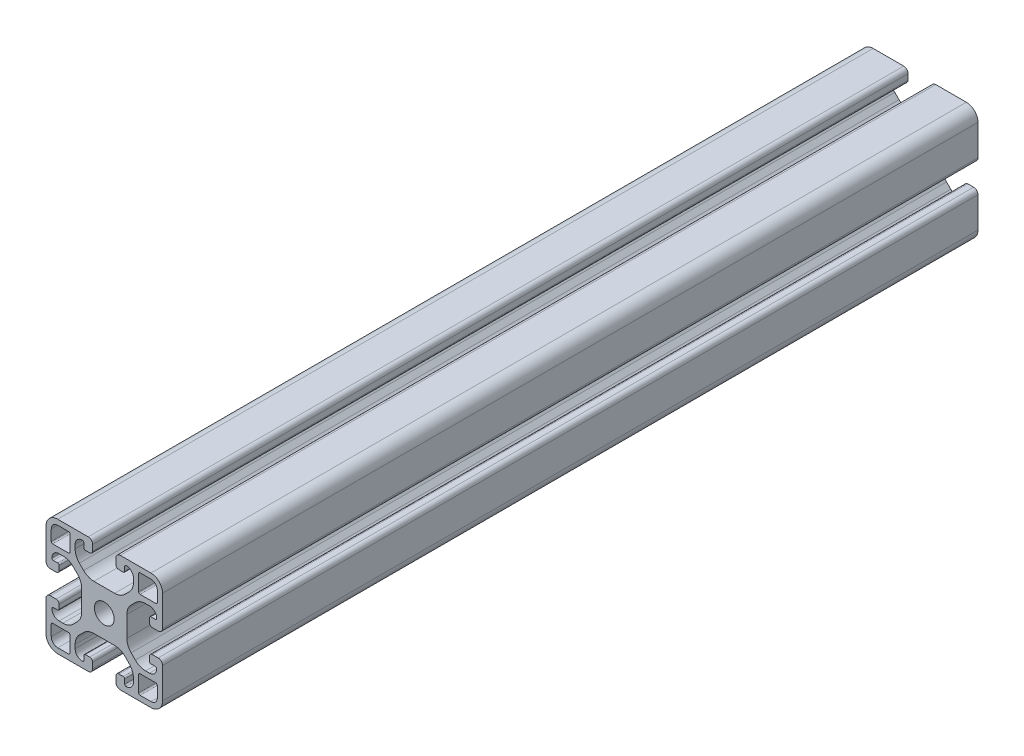
SolidWorks part; units mm, degrees
ref_plane "Plan de face" through (0, 0, 0) normal (0, 0, 1) x (1, 0, 0)
ref_plane "Plan de dessus" through (0, 0, 0) normal (0, 1, 0) x (1, 0, 0)
ref_plane "Plan de droite" through (0, 0, 0) normal (1, 0, 0) x (0, 0, -1)
ref_plane "Plan1" through (0, 0, -30) normal (0, 0, -1) x (-1, 0, 0)
sketch "Esquisse1" plane through (0, 0, -30) normal (0, 0, -1) x (-1, 0, 0)
  line L0 (-4.5, 15) -> (-4.5, 13.5)
  line L1 (-4, 13) -> (-2.5, 13)
  line L2 (-4.5, 10) -> (-5.8076, 10)
  line L3 (-9.3431, 11.4645) -> (-10.7855, 12.9069)
  line L4 (-12.25, 16.4424) -> (-12.25, 23.5576)
  line L5 (-10.7855, 27.0931) -> (-9.3431, 28.5355)
  line L6 (-5.8076, 30) -> (-4.5, 30)
  line L7 (-2.5, 27) -> (-4, 27)
  line L8 (-4.5, 26.5) -> (-4.5, 25)
  line L9 (-3.5, 24) -> (-1.5, 24)
  line L10 (0, 25.5) -> (0, 36)
  line L11 (-4, 40) -> (-14.5, 40)
  line L12 (-16, 38.5) -> (-16, 36.5)
  line L13 (-15, 35.5) -> (-13.5, 35.5)
  line L14 (-13, 36) -> (-13, 37.5)
  line L15 (-10, 35.5) -> (-10, 34.1924)
  line L16 (-11.4645, 30.6569) -> (-12.9069, 29.2145)
  line L17 (-16.4424, 27.75) -> (-23.5576, 27.75)
  line L18 (-27.0931, 29.2145) -> (-28.5355, 30.6569)
  line L19 (-30, 34.1924) -> (-30, 35.5)
  line L20 (-27, 37.5) -> (-27, 36)
  line L21 (-26.5, 35.5) -> (-25, 35.5)
  line L22 (-24, 36.5) -> (-24, 38.5)
  line L23 (-25.5, 40) -> (-36, 40)
  line L24 (-40, 36) -> (-40, 25.5)
  line L25 (-38.5, 24) -> (-36.5, 24)
  line L26 (-35.5, 25) -> (-35.5, 26.5)
  line L27 (-36, 27) -> (-37.5, 27)
  line L28 (-35.5, 30) -> (-34.1924, 30)
  line L29 (-30.6569, 28.5355) -> (-29.2145, 27.0931)
  line L30 (-27.75, 23.5576) -> (-27.75, 16.4424)
  line L31 (-29.2145, 12.9069) -> (-30.6569, 11.4645)
  line L32 (-34.1924, 10) -> (-35.5, 10)
  line L33 (-37.5, 13) -> (-36, 13)
  line L34 (-35.5, 13.5) -> (-35.5, 15)
  line L35 (-36.5, 16) -> (-38.5, 16)
  line L36 (-40, 14.5) -> (-40, 4)
  line L37 (-36, 0) -> (-25.5, 0)
  line L38 (-24, 1.5) -> (-24, 3.5)
  line L39 (-25, 4.5) -> (-26.5, 4.5)
  line L40 (-27, 4) -> (-27, 2.5)
  line L41 (-30, 4.5) -> (-30, 5.8076)
  line L42 (-28.5355, 9.3431) -> (-27.0931, 10.7855)
  line L43 (-23.5576, 12.25) -> (-16.4424, 12.25)
  line L44 (-12.9069, 10.7855) -> (-11.4645, 9.3431)
  line L45 (-10, 5.8076) -> (-10, 4.5)
  line L46 (-13, 2.5) -> (-13, 4)
  line L47 (-13.5, 4.5) -> (-15, 4.5)
  line L48 (-16, 3.5) -> (-16, 1.5)
  line L49 (-14.5, 0) -> (-4, 0)
  line L50 (0, 4) -> (0, 14.5)
  line L51 (-1.5, 16) -> (-3.5, 16)
  line L52 (-4, 1.8) -> (-7.7, 1.8)
  line L53 (-8.2, 2.3) -> (-8.2, 7.7)
  line L54 (-7.7, 8.2) -> (-2.3, 8.2)
  line L55 (-1.8, 7.7) -> (-1.8, 4)
  line L56 (-38.2, 4) -> (-38.2, 7.7)
  line L57 (-37.7, 8.2) -> (-32.3, 8.2)
  line L58 (-31.8, 7.7) -> (-31.8, 2.3)
  line L59 (-32.3, 1.8) -> (-36, 1.8)
  line L60 (-36, 38.2) -> (-32.3, 38.2)
  line L61 (-31.8, 37.7) -> (-31.8, 32.3)
  line L62 (-32.3, 31.8) -> (-37.7, 31.8)
  line L63 (-38.2, 32.3) -> (-38.2, 36)
  line L64 (-1.8, 36) -> (-1.8, 32.3)
  line L65 (-2.3, 31.8) -> (-7.7, 31.8)
  line L66 (-8.2, 32.3) -> (-8.2, 37.7)
  line L67 (-7.7, 38.2) -> (-4, 38.2)
  arc A0 (-4.5, 13.5) -> (-4, 13) centre (-4, 13.5) ccw
  arc A1 (-2.5, 13) -> (-2, 12.5) centre (-2.5, 12.5) cw
  arc A2 (-2, 12.5) -> (-4.5, 10) centre (-4.5, 12.5) cw
  arc A3 (-5.8076, 10) -> (-9.3431, 11.4645) centre (-5.8076, 15) cw
  arc A4 (-10.7855, 12.9069) -> (-12.25, 16.4424) centre (-7.25, 16.4424) cw
  arc A5 (-12.25, 23.5576) -> (-10.7855, 27.0931) centre (-7.25, 23.5576) cw
  arc A6 (-9.3431, 28.5355) -> (-5.8076, 30) centre (-5.8076, 25) cw
  arc A7 (-4.5, 30) -> (-2, 27.5) centre (-4.5, 27.5) cw
  arc A8 (-2, 27.5) -> (-2.5, 27) centre (-2.5, 27.5) cw
  arc A9 (-4, 27) -> (-4.5, 26.5) centre (-4, 26.5) ccw
  arc A10 (-4.5, 25) -> (-3.5, 24) centre (-3.5, 25) ccw
  arc A11 (-1.5, 24) -> (0, 25.5) centre (-1.5, 25.5) ccw
  arc A12 (0, 36) -> (-4, 40) centre (-4, 36) ccw
  arc A13 (-14.5, 40) -> (-16, 38.5) centre (-14.5, 38.5) ccw
  arc A14 (-16, 36.5) -> (-15, 35.5) centre (-15, 36.5) ccw
  arc A15 (-13.5, 35.5) -> (-13, 36) centre (-13.5, 36) ccw
  arc A16 (-13, 37.5) -> (-12.5, 38) centre (-12.5, 37.5) cw
  arc A17 (-12.5, 38) -> (-10, 35.5) centre (-12.5, 35.5) cw
  arc A18 (-10, 34.1924) -> (-11.4645, 30.6569) centre (-15, 34.1924) cw
  arc A19 (-12.9069, 29.2145) -> (-16.4424, 27.75) centre (-16.4424, 32.75) cw
  arc A20 (-23.5576, 27.75) -> (-27.0931, 29.2145) centre (-23.5576, 32.75) cw
  arc A21 (-28.5355, 30.6569) -> (-30, 34.1924) centre (-25, 34.1924) cw
  arc A22 (-30, 35.5) -> (-27.5, 38) centre (-27.5, 35.5) cw
  arc A23 (-27.5, 38) -> (-27, 37.5) centre (-27.5, 37.5) cw
  arc A24 (-27, 36) -> (-26.5, 35.5) centre (-26.5, 36) ccw
  arc A25 (-25, 35.5) -> (-24, 36.5) centre (-25, 36.5) ccw
  arc A26 (-24, 38.5) -> (-25.5, 40) centre (-25.5, 38.5) ccw
  arc A27 (-36, 40) -> (-40, 36) centre (-36, 36) ccw
  arc A28 (-40, 25.5) -> (-38.5, 24) centre (-38.5, 25.5) ccw
  arc A29 (-36.5, 24) -> (-35.5, 25) centre (-36.5, 25) ccw
  arc A30 (-35.5, 26.5) -> (-36, 27) centre (-36, 26.5) ccw
  arc A31 (-37.5, 27) -> (-38, 27.5) centre (-37.5, 27.5) cw
  arc A32 (-38, 27.5) -> (-35.5, 30) centre (-35.5, 27.5) cw
  arc A33 (-34.1924, 30) -> (-30.6569, 28.5355) centre (-34.1924, 25) cw
  arc A34 (-29.2145, 27.0931) -> (-27.75, 23.5576) centre (-32.75, 23.5576) cw
  arc A35 (-27.75, 16.4424) -> (-29.2145, 12.9069) centre (-32.75, 16.4424) cw
  arc A36 (-30.6569, 11.4645) -> (-34.1924, 10) centre (-34.1924, 15) cw
  arc A37 (-35.5, 10) -> (-38, 12.5) centre (-35.5, 12.5) cw
  arc A38 (-38, 12.5) -> (-37.5, 13) centre (-37.5, 12.5) cw
  arc A39 (-36, 13) -> (-35.5, 13.5) centre (-36, 13.5) ccw
  arc A40 (-35.5, 15) -> (-36.5, 16) centre (-36.5, 15) ccw
  arc A41 (-38.5, 16) -> (-40, 14.5) centre (-38.5, 14.5) ccw
  arc A42 (-40, 4) -> (-36, 0) centre (-36, 4) ccw
  arc A43 (-25.5, 0) -> (-24, 1.5) centre (-25.5, 1.5) ccw
  arc A44 (-24, 3.5) -> (-25, 4.5) centre (-25, 3.5) ccw
  arc A45 (-26.5, 4.5) -> (-27, 4) centre (-26.5, 4) ccw
  arc A46 (-27, 2.5) -> (-27.5, 2) centre (-27.5, 2.5) cw
  arc A47 (-27.5, 2) -> (-30, 4.5) centre (-27.5, 4.5) cw
  arc A48 (-30, 5.8076) -> (-28.5355, 9.3431) centre (-25, 5.8076) cw
  arc A49 (-27.0931, 10.7855) -> (-23.5576, 12.25) centre (-23.5576, 7.25) cw
  arc A50 (-16.4424, 12.25) -> (-12.9069, 10.7855) centre (-16.4424, 7.25) cw
  arc A51 (-11.4645, 9.3431) -> (-10, 5.8076) centre (-15, 5.8076) cw
  arc A52 (-10, 4.5) -> (-12.5, 2) centre (-12.5, 4.5) cw
  arc A53 (-12.5, 2) -> (-13, 2.5) centre (-12.5, 2.5) cw
  arc A54 (-13, 4) -> (-13.5, 4.5) centre (-13.5, 4) ccw
  arc A55 (-15, 4.5) -> (-16, 3.5) centre (-15, 3.5) ccw
  arc A56 (-16, 1.5) -> (-14.5, 0) centre (-14.5, 1.5) ccw
  arc A57 (-4, 0) -> (0, 4) centre (-4, 4) ccw
  arc A58 (0, 14.5) -> (-1.5, 16) centre (-1.5, 14.5) ccw
  arc A59 (-3.5, 16) -> (-4.5, 15) centre (-3.5, 15) ccw
  circle A60 centre (-20, 20) radius 3.4
  arc A61 (-1.8, 4) -> (-4, 1.8) centre (-4, 4) cw
  arc A62 (-7.7, 1.8) -> (-8.2, 2.3) centre (-7.7, 2.3) cw
  arc A63 (-8.2, 7.7) -> (-7.7, 8.2) centre (-7.7, 7.7) cw
  arc A64 (-2.3, 8.2) -> (-1.8, 7.7) centre (-2.3, 7.7) cw
  arc A65 (-36, 1.8) -> (-38.2, 4) centre (-36, 4) cw
  arc A66 (-38.2, 7.7) -> (-37.7, 8.2) centre (-37.7, 7.7) cw
  arc A67 (-32.3, 8.2) -> (-31.8, 7.7) centre (-32.3, 7.7) cw
  arc A68 (-31.8, 2.3) -> (-32.3, 1.8) centre (-32.3, 2.3) cw
  arc A69 (-38.2, 36) -> (-36, 38.2) centre (-36, 36) cw
  arc A70 (-32.3, 38.2) -> (-31.8, 37.7) centre (-32.3, 37.7) cw
  arc A71 (-31.8, 32.3) -> (-32.3, 31.8) centre (-32.3, 32.3) cw
  arc A72 (-37.7, 31.8) -> (-38.2, 32.3) centre (-37.7, 32.3) cw
  arc A73 (-4, 38.2) -> (-1.8, 36) centre (-4, 36) cw
  arc A74 (-1.8, 32.3) -> (-2.3, 31.8) centre (-2.3, 32.3) cw
  arc A75 (-7.7, 31.8) -> (-8.2, 32.3) centre (-7.7, 32.3) cw
  arc A76 (-8.2, 37.7) -> (-7.7, 38.2) centre (-7.7, 37.7) cw
extrude "Boss.-Extru.1" add sketch "Esquisse1" against normal blind 279.85
